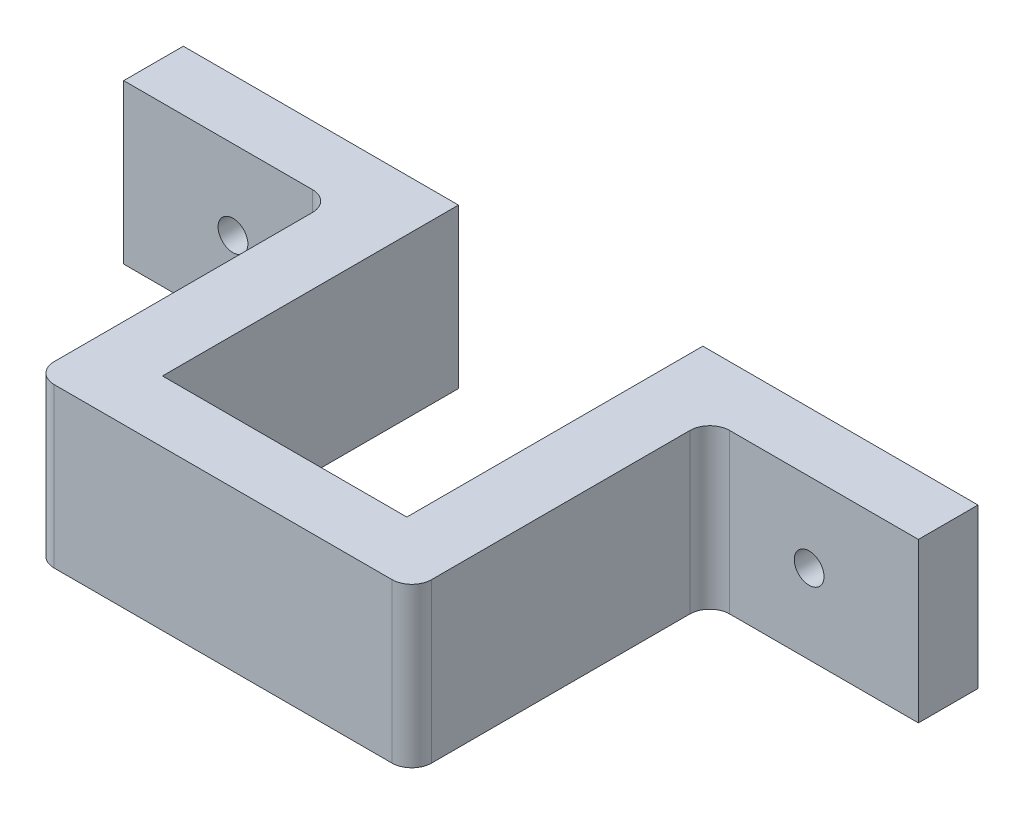
SolidWorks part; units mm, degrees
ref_plane "Front Plane" through (0, 0, 0) normal (0, 0, 1) x (1, 0, 0)
ref_plane "Top Plane" through (0, 0, 0) normal (0, 1, 0) x (1, 0, 0)
ref_plane "Right Plane" through (0, 0, 0) normal (1, 0, 0) x (0, 0, -1)
sketch "Sketch1" plane through (0, 0, 0) normal (0, 0, 1) x (1, 0, 0)
  line L0 (14.5, 0) -> (-14.5, 0)
  line L1 (20, -4) -> (-20, -4)
  line L2 (20, -4) -> (20, 4)
  line L3 (20, 4) -> (-20, 4)
  line L4 (-20, -4) -> (-20, 4)
  line L5 (20, -4) -> (-20, 4) construction
  line L6 (20, 4) -> (-20, -4) construction
  circle A0 centre (-14.5, 0) radius 0.75
  circle A1 centre (14.5, 0) radius 0.75
  point P0 (0, 0)
  point P9 (0, 0)
  dimension "D4" = 1.5
  dimension "D5" = 1.5
  dimension "D1" = 40
  dimension "D2" = 8
  dimension "D3" = 29
extrude "Boss-Extrude1" add sketch "Sketch1" along normal blind 3
sketch "Sketch2" plane through (0, 0, 3) normal (0, 0, 1) x (1, 0, 0)
  line L0 (20, 4) -> (-20, 4) construction
  line L1 (9.5, -4) -> (-9.5, -4)
  line L2 (9.5, -4) -> (9.5, 4)
  line L3 (9.5, 4) -> (-9.5, 4)
  line L4 (-9.5, -4) -> (-9.5, 4)
  line L5 (9.5, -4) -> (-9.5, 4) construction
  line L6 (9.5, 4) -> (-9.5, -4) construction
  line L7 (-20, -4) -> (-20, 4) construction
  point P0 (0, 0)
  dimension "D1" = 10.5
extrude "Boss-Extrude2" add sketch "Sketch2" along normal blind 15
sketch "Sketch3" plane through (0, -4, 0) normal (0, -1, 0) x (1, 0, 0)
  line L1 (6.15, -14.9) -> (-6.15, -14.9)
  line L2 (6.15, -14.9) -> (6.15, 14.9)
  line L3 (6.15, 14.9) -> (-6.15, 14.9)
  line L4 (-6.15, -14.9) -> (-6.15, 14.9)
  line L5 (6.15, -14.9) -> (-6.15, 14.9) construction
  line L6 (6.15, 14.9) -> (-6.15, -14.9) construction
  point P0 (0, 0)
  dimension "D1" = 12.3
  dimension "D2" = 29.8
extrude "Cut-Extrude1" cut sketch "Sketch3" against normal up to surface (8 mm away) up to face at (0, 4, 6)
fillet "Fillet1" radius 1 4 edges at (-9.5, 0, 18) (9.5, 0, 18) (9.5, 0, 3) (-9.5, 0, 3)
